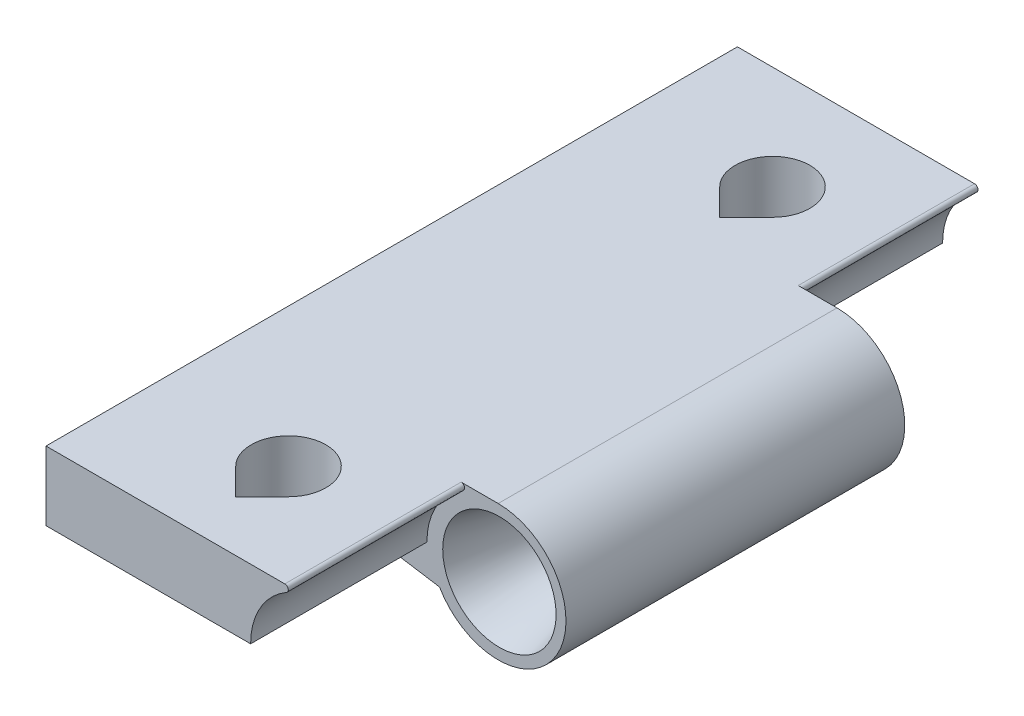
SolidWorks part; units mm, degrees
ref_plane "Front Plane" through (0, 0, 0) normal (0, 0, 1) x (1, 0, 0)
ref_plane "Top Plane" through (0, 0, 0) normal (0, 1, 0) x (1, 0, 0)
ref_plane "Right Plane" through (0, 0, 0) normal (1, 0, 0) x (0, 0, -1)
ref_plane "Plane1" through (0, 0, -25) normal (0, 0, -1) x (-1, 0, 0)
sketch "Sketch1" plane through (0, 0, -25) normal (0, 0, -1) x (-1, 0, 0)
  line L0 (5.2, 0) -> (20.0381, 0)
  line L1 (20.0381, 0) -> (20.0381, 4.8713)
  line L2 (20.0381, 4.8713) -> (2.8906, 4.8713)
  arc A0 (2.8906, 4.8713) -> (2.7577, 4.4085) centre (2.8906, 4.6209) ccw
  arc A1 (2.7577, 4.4085) -> (5.2, 0) centre (0, 0) cw
  dimension "D1" = 5.2
  dimension "D2" = 4.8713
extrude "Boss-Extrude1" add sketch "Sketch1" against normal blind 12.75
sketch "Sketch2" plane through (0, 0, -12.25) normal (0, 0, 1) x (1, 0, 0)
  line L0 (-20.0381, 4.8713) -> (-0.0866, 4.8713)
  line L1 (-4.3301, -2.4787) -> (-20.0381, 0.0213)
  line L2 (-20.0381, 0.0213) -> (-20.0381, 4.8713)
  line L3 (-20.0381, 4.8713) -> (-2.8906, 4.8713) construction
  line L4 (-20.0381, 0) -> (-20.0381, 4.8713) construction
  arc A0 (-0.0866, 4.8713) -> (-4.3301, -2.4787) centre (-0.0866, -0.0287) cw
  dimension "D1" = 4.9
extrude "Boss-Extrude2" add sketch "Sketch2" along normal blind 24.5
sketch "Sketch3" plane through (0, 0, 12.25) normal (0, 0, 1) x (1, 0, 0)
  line L0 (-20.0381, 4.8713) -> (-2.7676, 4.8713)
  line L1 (-5.24, -0.12) -> (-20.0381, -0.12)
  line L2 (-20.0381, -0.12) -> (-20.0381, 4.8713)
  line L3 (-0.0866, 4.8713) -> (-20.0381, 4.8713) construction
  line L4 (-20.0381, 4.8713) -> (-20.0381, 0.0213) construction
  arc A0 (-2.7676, 4.8713) -> (-2.6416, 4.4054) centre (-2.7676, 4.6213) cw
  arc A1 (-2.6416, 4.4054) -> (-5.24, -0.12) centre (0, -0.12) ccw
  dimension "D1" = 5.24
extrude "Boss-Extrude3" add sketch "Sketch3" along normal blind 12.75
sketch "Sketch4" plane through (0, 4.8713, 0) normal (0, 1, 0) x (-1, 0, 0)
  line L0 (10, -13.6816) -> (8.0908, -15.5908)
  line L1 (11.9092, -15.5908) -> (10, -13.6816)
  arc A0 (8.0908, -15.5908) -> (11.9092, -15.5908) centre (10, -17.5) ccw
extrude "Cut-Extrude1" cut sketch "Sketch4" against normal through all
sketch "Sketch5" plane through (0, 4.8713, 0) normal (0, 1, 0) x (-1, 0, 0)
  line L0 (10, 21.3184) -> (8.0908, 19.4092)
  line L1 (11.9092, 19.4092) -> (10, 21.3184)
  arc A0 (8.0908, 19.4092) -> (11.9092, 19.4092) centre (10, 17.5) ccw
extrude "Cut-Extrude2" cut sketch "Sketch5" against normal through all
ref_plane "Plane2" through (0, 0, 0) normal (0, -1, 0) x (1, 0, 0)
sketch "Sketch6" plane through (0, 0, 0) normal (0, -1, 0) x (1, 0, 0)
  line L0 (4.1, 12.25) -> (0, 12.25)
  line L1 (0, 12.25) -> (0, -12.25)
  line L2 (0, -12.25) -> (4.1829, -12.25)
  line L3 (0, 12.25) -> (0, -12.25) construction
  arc A0 (4.1829, -12.25) -> (4.1, 12.25) centre (43.0208, 0.1316) cw
  dimension "D1" = 4.1
revolve "Cut-Revolve1" cut sketch "Sketch6" angle 360 about L3
fillet "Fillet2" [suppressed] radius 0.25
